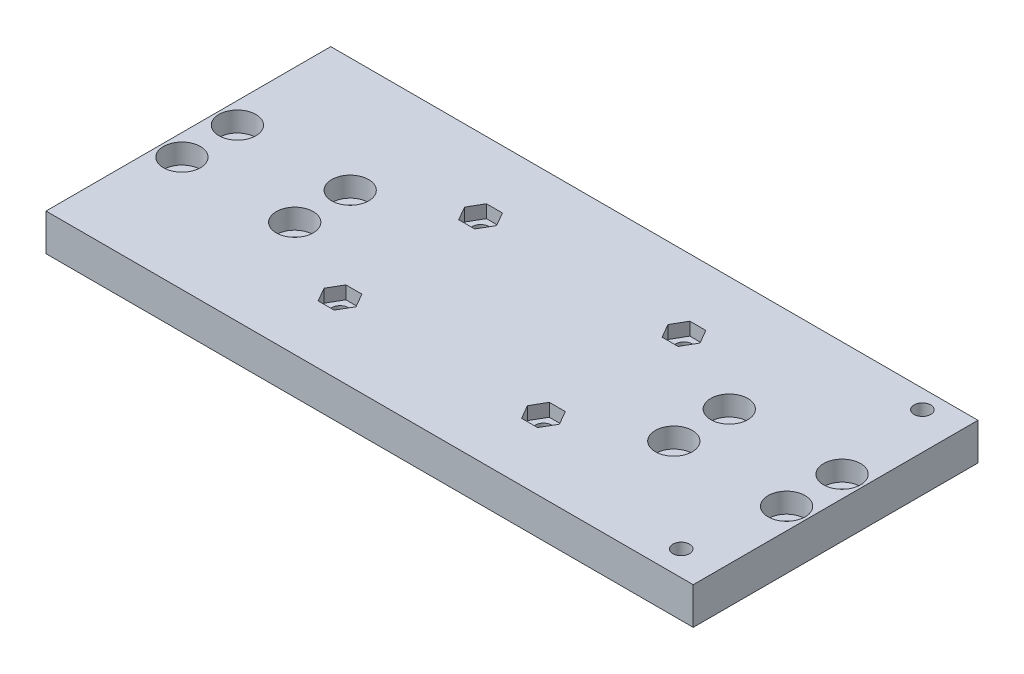
SolidWorks part; units mm, degrees
ref_plane "Front Plane" through (0, 0, 0) normal (0, 0, 1) x (1, 0, 0)
ref_plane "Top Plane" through (0, 0, 0) normal (0, 1, 0) x (1, 0, 0)
ref_plane "Right Plane" through (0, 0, 0) normal (1, 0, 0) x (0, 0, -1)
sketch "Sketch1" plane through (0, 0, 0) normal (0, 1, 0) x (1, 0, 0)
  line L1 (-87.5, -38.5) -> (87.5, -38.5)
  line L2 (-87.5, -38.5) -> (-87.5, 38.5)
  line L3 (-87.5, 38.5) -> (87.5, 38.5)
  line L4 (87.5, -38.5) -> (87.5, 38.5)
  line L5 (-87.5, -38.5) -> (87.5, 38.5) construction
  line L6 (-87.5, 38.5) -> (87.5, -38.5) construction
  point P0 (0, 0)
  dimension "D1" = 175
  dimension "D2" = 77
extrude "Boss-Extrude1" add sketch "Sketch1" along normal blind 10
sketch "Sketch3" plane through (0, 10, 0) normal (0, 1, 0) x (1, 0, 0)
  line L0 (-87.5, 38.5) -> (-87.5, -38.5) construction
  line L1 (87.5, 38.5) -> (-87.5, 38.5) construction
  line L2 (-87.5, -38.5) -> (87.5, -38.5) construction
  line L3 (0, -55) -> (0, 55) construction
  point P0 (-81.75, -33.5)
  point P1 (-81.75, -7.5)
  point P2 (-51.25, -7.5)
  point P3 (-51.25, -33.5)
  point P4 (-81.75, 33.5)
  point P5 (-81.75, 7.5)
  point P6 (-51.25, 7.5)
  point P7 (-51.25, 33.5)
  point P16 (51.25, 33.5)
  point P17 (51.25, 7.5)
  point P18 (81.75, 7.5)
  point P19 (81.75, 33.5)
  point P20 (51.25, -33.5)
  point P21 (51.25, -7.5)
  point P22 (81.75, -7.5)
  point P23 (81.75, -33.5)
  dimension "D1" = 30.5
  dimension "D2" = 26
  dimension "D3" = 5.75
  dimension "D4" = 5
  dimension "D5" = 5
  dimension "D6" = 26
hole_wizard "CBORE for M5 Hex Socket Head Cap Screw3" positions "3DSketch2" profile "Sketch5" counterbore size "M5" standard "DIN" end condition up to next
sketch3d "3DSketch2"
  point P0 (-81.75, 10, 7.5)
  point P3 (-81.75, 10, -7.5)
  point P6 (-51.25, 10, -7.5)
  point P9 (-51.25, 10, 7.5)
  point P13 (51.25, 10, 7.5)
  point P16 (51.25, 10, -7.5)
  point P19 (81.75, 10, -7.5)
  point P22 (81.75, 10, 7.5)
sketch "Sketch5" plane through (-81.75, 10, 7.5) normal (1, 0, 0) x (0, 0, 1)
  line L0 (0, 0) -> (0, 10)
  line L1 (0, 10) -> (2.75, 10)
  line L3 (2.75, 10) -> (2.75, 5.4)
  line L4 (2.75, 5.4) -> (5, 5.4)
  line L5 (5, 5.4) -> (5, 0)
  line L7 (5, 0) -> (0, 0)
  line L11 (0, -6.35) -> (0, 107.95) construction
  dimension "Thru Hole Dia." = 5.5
  dimension "Thru Hole Depth" = 10
  dimension "C'Bore Dia." = 10
  dimension "C'Bore Depth" = 5.4
sketch "Sketch7" plane through (0, 10, 0) normal (0, 1, 0) x (1, 0, 0)
  line L0 (87.5, -38.5) -> (87.5, 38.5) construction
  line L1 (-87.5, -38.5) -> (87.5, -38.5) construction
  point P0 (77.5, 33.46)
  point P1 (77.5, -31.75)
  point P4 (0, 0)
  dimension "D1" = 65.21
  dimension "D2" = 6.75
  dimension "D3" = 10
hole_wizard "M4 Clearance Hole1" positions "3DSketch3" profile "Sketch8" hole size "M4" standard "DIN" end condition up to next
sketch3d "3DSketch3"
  point P0 (77.5, 10, 31.75)
  point P3 (77.5, 10, -33.46)
sketch "Sketch8" plane through (77.5, 10, 31.75) normal (1, 0, 0) x (0, 0, 1)
  line L0 (0, 0) -> (0, 10)
  line L1 (0, 10) -> (2.25, 10)
  line L2 (2.25, 10) -> (2.25, 0)
  line L5 (2.25, 0) -> (0, 0)
  line L11 (0, -6.35) -> (0, 107.95) construction
  dimension "Thru Hole Dia." = 4.5
  dimension "Thru Hole Depth" = 10
sketch "Sketch9" plane through (0, 0, 0) normal (0, -1, 0) x (1, 0, 0)
  line L1 (81.8301, 31.75) -> (79.6651, 35.5)
  line L2 (79.6651, 35.5) -> (75.3349, 35.5)
  line L3 (75.3349, 35.5) -> (73.1699, 31.75)
  line L4 (73.1699, 31.75) -> (75.3349, 28)
  line L5 (75.3349, 28) -> (79.6651, 28)
  line L6 (79.6651, 28) -> (81.8301, 31.75)
  line L7 (79.6651, -29.71) -> (75.3349, -29.71)
  line L8 (75.3349, -29.71) -> (73.1699, -33.46)
  line L9 (73.1699, -33.46) -> (75.3349, -37.21)
  line L10 (75.3349, -37.21) -> (79.6651, -37.21)
  line L11 (79.6651, -37.21) -> (81.8301, -33.46)
  line L12 (81.8301, -33.46) -> (79.6651, -29.71)
  circle A0 centre (77.5, 31.75) radius 3.75 construction
  circle A1 centre (77.5, -33.46) radius 3.75 construction
  point P10 (79.2365, 30.0171)
  point P19 (77.5, 28)
  point P20 (77.5, -37.21)
  dimension "D1" = 7.5
  dimension "D2" = 7.5
extrude "Cut-Extrude1" cut sketch "Sketch9" against normal blind 3.5
sketch "Sketch10" plane through (0, 0, 0) normal (0, -1, 0) x (1, 0, 0)
  line L0 (87.5, -38.5) -> (-87.5, -38.5) construction
  line L1 (-87.5, -38.5) -> (-87.5, 38.5) construction
  point P0 (-27.5, 19)
  point P1 (-27.5, -19)
  point P2 (27.5, 19)
  point P3 (27.5, -19)
  point P8 (0, 0)
  point P9 (0, 0)
  point P10 (0, 0)
  point P11 (0, 0)
  dimension "D1" = 19.5
  dimension "D2" = 60
  dimension "D3" = 55
  dimension "D4" = 38
hole_wizard "M4 Clearance Hole2" positions "3DSketch4" profile "Sketch11" hole size "M4" standard "DIN" end condition up to next
sketch3d "3DSketch4"
  point P0 (-27.5, 0, 19)
  point P3 (27.5, 0, 19)
  point P6 (-27.5, 0, -19)
  point P9 (27.5, 0, -19)
sketch "Sketch11" plane through (-27.5, 0, 19) normal (1, 0, 0) x (0, 0, -1)
  line L0 (0, 0) -> (0, 10)
  line L1 (0, 10) -> (2.25, 10)
  line L2 (2.25, 10) -> (2.25, 0)
  line L5 (2.25, 0) -> (0, 0)
  line L11 (0, -6.35) -> (0, 107.95) construction
  dimension "Thru Hole Dia." = 4.5
  dimension "Thru Hole Depth" = 10
sketch "Sketch12" plane through (0, 10, 0) normal (0, 1, 0) x (1, 0, 0)
  line L1 (-23.1699, 19) -> (-25.3349, 22.75)
  line L2 (-25.3349, 22.75) -> (-29.6651, 22.75)
  line L3 (-29.6651, 22.75) -> (-31.8301, 19)
  line L4 (-31.8301, 19) -> (-29.6651, 15.25)
  line L5 (-29.6651, 15.25) -> (-25.3349, 15.25)
  line L6 (-25.3349, 15.25) -> (-23.1699, 19)
  line L7 (31.8301, 19) -> (29.6651, 22.75)
  line L8 (29.6651, 22.75) -> (25.3349, 22.75)
  line L9 (25.3349, 22.75) -> (23.1699, 19)
  line L10 (23.1699, 19) -> (25.3349, 15.25)
  line L11 (25.3349, 15.25) -> (29.6651, 15.25)
  line L12 (29.6651, 15.25) -> (31.8301, 19)
  line L13 (31.8301, -19) -> (29.6651, -15.25)
  line L14 (29.6651, -15.25) -> (25.3349, -15.25)
  line L15 (25.3349, -15.25) -> (23.1699, -19)
  line L16 (23.1699, -19) -> (25.3349, -22.75)
  line L17 (25.3349, -22.75) -> (29.6651, -22.75)
  line L18 (29.6651, -22.75) -> (31.8301, -19)
  line L19 (-23.1699, -19) -> (-25.3349, -15.25)
  line L20 (-25.3349, -15.25) -> (-29.6651, -15.25)
  line L21 (-29.6651, -15.25) -> (-31.8301, -19)
  line L22 (-31.8301, -19) -> (-29.6651, -22.75)
  line L23 (-29.6651, -22.75) -> (-25.3349, -22.75)
  line L24 (-25.3349, -22.75) -> (-23.1699, -19)
  circle A0 centre (-27.5, 19) radius 3.75 construction
  circle A1 centre (27.5, 19) radius 3.75 construction
  circle A2 centre (27.5, -19) radius 3.75 construction
  circle A3 centre (-27.5, -19) radius 3.75 construction
  point P28 (-27.5, 15.25)
  point P37 (-27.5, -22.75)
  point P38 (0, 0)
  point P39 (27.5, 15.25)
  point P40 (27.5, -22.75)
  dimension "D1" = 7.5
extrude "Cut-Extrude2" cut sketch "Sketch12" against normal blind 3.5
